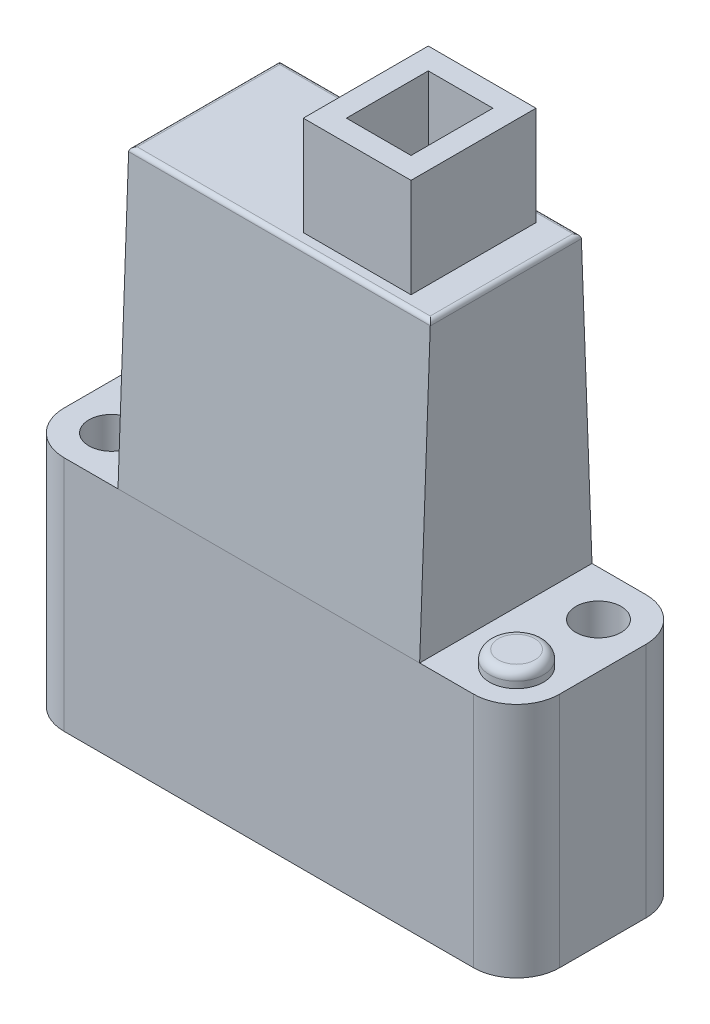
SolidWorks part; units mm, degrees
ref_plane "Front Plane" through (0, 0, 0) normal (0, 0, 1) x (1, 0, 0)
ref_plane "Top Plane" through (0, 0, 0) normal (0, 1, 0) x (1, 0, 0)
ref_plane "Right Plane" through (0, 0, 0) normal (1, 0, 0) x (0, 0, -1)
sketch "Sketch1" plane through (0, 0, 0) normal (0, 0, 1) x (1, 0, 0)
  line L1 (-11.5, 11) -> (11.5, 11)
  line L2 (-11.5, 11) -> (-11.5, 0)
  line L3 (-11.5, 0) -> (11.5, 0)
  line L4 (11.5, 11) -> (11.5, 0)
  line L5 (-7, 24.5) -> (7, 24.5)
  line L6 (-7, 24.5) -> (-7, 11)
  line L7 (-7, 11) -> (7, 11)
  line L8 (7, 24.5) -> (7, 11)
  point P8 (0, 11)
  point P9 (0, 11)
  point P10 (0, 0)
  dimension "D1" = 24.5
  dimension "D2" = 23
  dimension "D3" = 11
  dimension "D4" = 14
extrude "Boss-Extrude1" add sketch "Sketch1" along normal mid plane 8 contours L8 L5 L6 L1 | L4 L1 L2 L3
fillet "Fillet1" radius 2 4 edges at (11.5, 5.5, -4) (11.5, 5.5, 4) (-11.5, 5.5, -4) (-11.5, 5.5, 4)
sketch "Sketch2" plane through (0, 0, 0) normal (1, 0, 0) x (0, 0, -1)
  line L0 (-4, 24.5) -> (-3.5, 24.5)
  line L1 (-4, 24.5) -> (4, 24.5) construction
  line L2 (-3.5, 24.5) -> (-4, 11)
  line L3 (-4, 11) -> (-4, 24.5)
  dimension "D1" = 0.5
extrude "Cut-Extrude1" cut sketch "Sketch2" against normal through all both and the other way through all
mirror "Mirror1" about plane through (0, 0, 0) normal (0, 0, 1) of "Cut-Extrude1"
fillet "Fillet2" radius 0.2 4 edges at (-7, 24.5, 0) (0, 24.5, -3.5) (7, 24.5, 0) (0, 24.5, 3.5)
sketch "Sketch3" plane through (0, 11, 0) normal (0, 1, 0) x (1, 0, 0)
  circle A0 centre (9.4, 1.9) radius 1.05
  circle A1 centre (-9.4, -1.9) radius 1.05
  dimension "D3" = 2.1
  dimension "D1" = 1.9
  dimension "D2" = 1.9
  dimension "D4" = 9.4
  dimension "D5" = 9.4
extrude "Cut-Extrude2" cut sketch "Sketch3" against normal through all
sketch "Sketch5" plane through (0, 11, 0) normal (0, 1, 0) x (1, 0, 0)
  circle A0 centre (9.4, -1.9) radius 1.25
  circle A1 centre (-9.4, 1.9) radius 1.25
  dimension "D5" = 2.5
  dimension "D6" = 2.5
  dimension "D1" = 1.9
  dimension "D2" = 1.9
  dimension "D3" = 9.4
  dimension "D4" = 9.4
extrude "Boss-Extrude2" add sketch "Sketch5" along normal blind 0.7
fillet "Fillet3" radius 0.4 2 edges at (-10.65, 11.7, -1.9) (8.15, 11.7, 1.9)
sketch "Sketch6" plane through (0, 24.5, 0) normal (0, 1, 0) x (1, 0, 0)
  line L0 (-7, -4) -> (-7, 4) construction
  line L1 (5.5, 2.9) -> (0.5, 2.9)
  line L2 (5.5, 2.9) -> (5.5, -2.9)
  line L3 (5.5, -2.9) -> (0.5, -2.9)
  line L4 (0.5, 2.9) -> (0.5, -2.9)
  line L5 (5.5, 2.9) -> (0.5, -2.9) construction
  line L6 (5.5, -2.9) -> (0.5, 2.9) construction
  line L7 (1.5, -1.9) -> (4.5, -1.9)
  line L8 (1.5, -1.9) -> (1.5, 1.9)
  line L9 (1.5, 1.9) -> (4.5, 1.9)
  line L10 (4.5, -1.9) -> (4.5, 1.9)
  line L11 (1.5, -1.9) -> (4.5, 1.9) construction
  line L12 (1.5, 1.9) -> (4.5, -1.9) construction
  point P0 (3, 0)
  point P5 (3, 0)
  point P10 (0, 0)
  point P11 (0, 0)
  dimension "D1" = 7.5
  dimension "D2" = 5
  dimension "D3" = 5.8
  dimension "D4" = 3.8
  dimension "D5" = 3
extrude "Boss-Extrude3" add sketch "Sketch6" along normal blind 4.6
sketch "Sketch7" plane through (0, 0, 0) normal (0, -1, 0) x (1, 0, 0)
  circle A0 centre (0, 0) radius 1.397
  circle A1 centre (5, 0) radius 1.397
  circle A2 centre (-5, 0) radius 1.397
  point P7 (0, 0)
  dimension "D1" = 5
  dimension "D2" = 5
  dimension "D3" = 2.794
extrude "Cut-Extrude3" cut sketch "Sketch7" against normal blind 0.762
sketch "Sketch9" plane through (0, 0, 0) normal (0, 0, 1) x (1, 0, 0)
  line L0 (0, 0) -> (0, -0.8912) construction
  line L1 (0, 0.762) -> (2.0427, 0.762) construction
  line L2 (-1.397, 0.762) -> (1.397, 0.762) construction
  circle A0 centre (0.8763, 0.254) radius 0.508
  point P9 (2.0427, 0.762)
  dimension "D1" = 1.7526
  dimension "D2" = 1.016
revolve "Revolve1" add sketch "Sketch9" angle 360 about L0
pattern_linear "LPattern5" count 2 spacing 5 along (-1, 0, 0) count 2 spacing 5 along (1, 0, 0) of bodies 108
